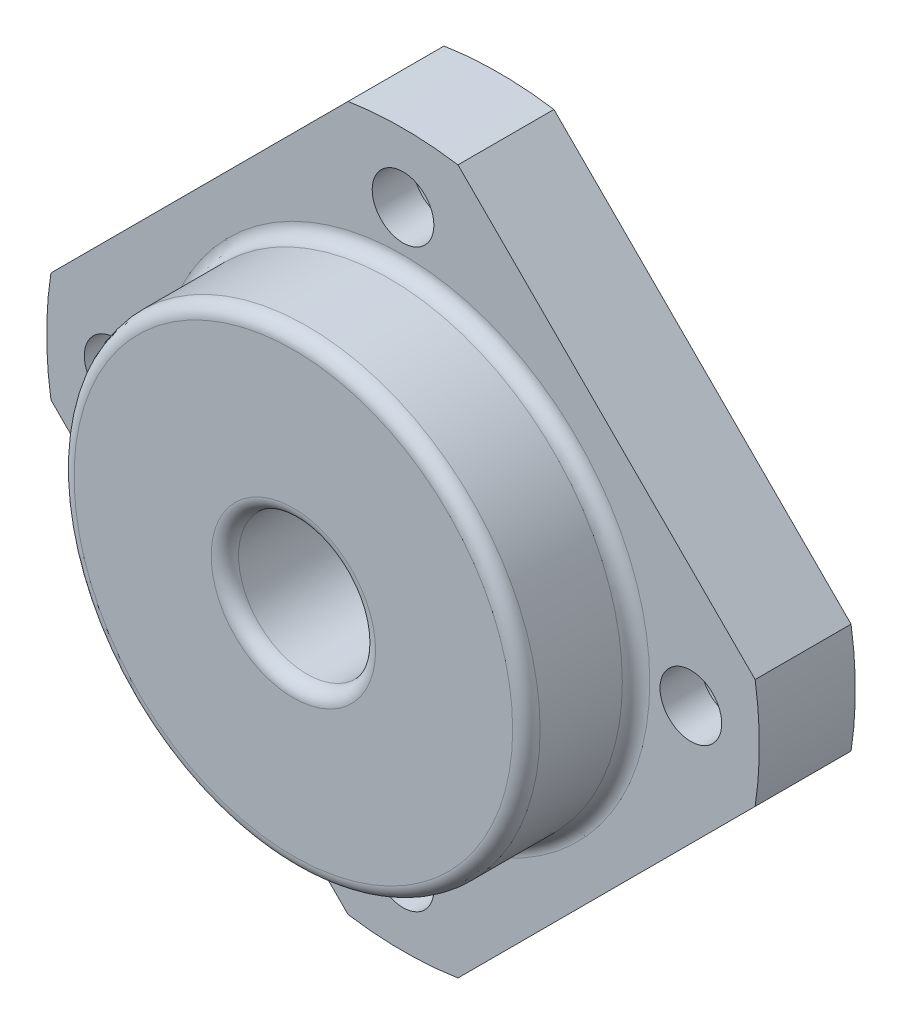
SolidWorks part; units mm, degrees
ref_plane "Front Plane" through (0, 0, 0) normal (0, 0, 1) x (1, 0, 0)
ref_plane "Top Plane" through (0, 0, 0) normal (0, 1, 0) x (1, 0, 0)
ref_plane "Right Plane" through (0, 0, 0) normal (1, 0, 0) x (0, 0, -1)
sketch "Sketch1" plane through (0, 0, 0) normal (0, 0, 1) x (1, 0, 0)
  line L1 (-14.8492, -14.8492) -> (-25.689, -4.0095)
  line L2 (-14.8492, -14.8492) -> (-4.0095, -25.689)
  line L4 (14.8492, 14.8492) -> (4.0095, 25.689)
  line L5 (14.8492, 14.8492) -> (25.689, 4.0095)
  line L6 (-14.8492, 14.8492) -> (-25.689, 4.0095)
  line L7 (-14.8492, 14.8492) -> (-4.0095, 25.689)
  line L8 (14.8492, -14.8492) -> (25.689, -4.0095)
  line L9 (14.8492, -14.8492) -> (4.0095, -25.689)
  arc A0 (-4.0095, -25.689) -> (4.0095, -25.689) centre (0, 0) ccw
  arc A8 (25.689, -4.0095) -> (25.689, 4.0095) centre (0, 0) ccw
  arc A9 (4.0095, 25.689) -> (-4.0095, 25.689) centre (0, 0) ccw
  arc A10 (-25.689, 4.0095) -> (-25.689, -4.0095) centre (0, 0) ccw
  dimension "D1" = 52
extrude "Boss-Extrude1" add sketch "Sketch1" along normal blind 7
sketch "Sketch2" plane through (0, 0, 0) normal (0, 0, -1) x (-1, 0, 0)
  circle A0 centre (0, 0) radius 21
  circle A1 centre (0, 21) radius 4
  circle A2 centre (-21, 0) radius 4
  circle A3 centre (0, -21) radius 4
  circle A4 centre (21, 0) radius 4
extrude "Cut-Extrude1" cut sketch "Sketch2" against normal blind 4 contours A2 | A1 | A4 | A3
sketch "Sketch3" plane through (0, 0, 4) normal (0, 0, -1) x (-1, 0, 0)
  circle A0 centre (0, 21) radius 2.25
  circle A1 centre (-21, 0) radius 2.25
  circle A2 centre (21, 0) radius 2.25
  circle A3 centre (0, -21) radius 2.25
  dimension "D1" = 4.5
extrude "Cut-Extrude2" cut sketch "Sketch3" against normal blind 4
sketch "Sketch4" plane through (0, 0, 7) normal (0, 0, 1) x (1, 0, 0)
  circle A0 centre (0, 0) radius 17
extrude "Boss-Extrude2" add sketch "Sketch4" along normal blind 8
sketch "Sketch5" plane through (0, 0, 15) normal (0, 0, 1) x (1, 0, 0)
  circle A0 centre (0, 0) radius 5
  dimension "D1" = 10
extrude "Cut-Extrude3" cut sketch "Sketch5" against normal blind 15
fillet "Fillet3" radius 1 3 edges at (17, 0, 7) (17, 0, 15) (5, 0, 15)
